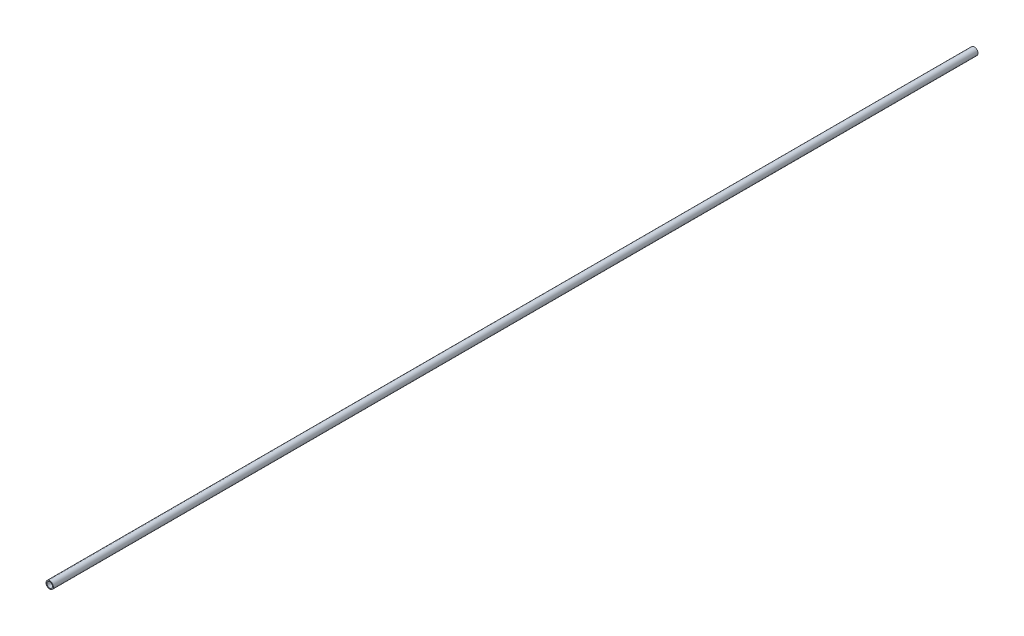
SolidWorks part; units mm, degrees
material "carbon fiber"
ref_plane "Front Plane" through (0, 0, 0) normal (0, 0, 1) x (1, 0, 0)
ref_plane "Top Plane" through (0, 0, 0) normal (0, 1, 0) x (1, 0, 0)
ref_plane "Right Plane" through (0, 0, 0) normal (1, 0, 0) x (0, 0, -1)
sketch "Эскиз1" plane through (0, 0, 0) normal (0, 0, 1) x (1, 0, 0)
  circle A0 centre (0, 0) radius 3
  circle A1 centre (0, 0) radius 4
  dimension "D1" = 1
  dimension "D2" = 6
extrude "Бобышка-Вытянуть1" add sketch "Эскиз1" along normal mid plane 1000
